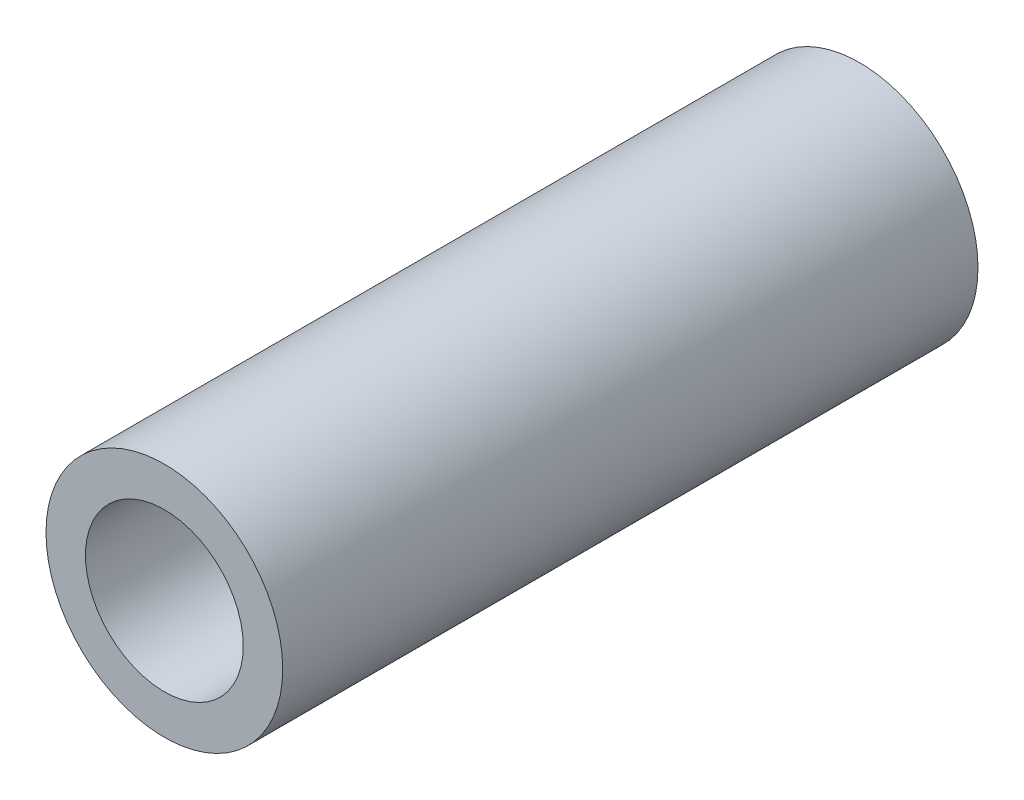
SolidWorks part; units mm, degrees
ref_plane "Front Plane" through (0, 0, 0) normal (0, 0, 1) x (1, 0, 0)
ref_plane "Top Plane" through (0, 0, 0) normal (0, 1, 0) x (1, 0, 0)
ref_plane "Right Plane" through (0, 0, 0) normal (1, 0, 0) x (0, 0, -1)
sketch "Эскиз1" plane through (0, 0, 0) normal (0, 0, 1) x (1, 0, 0)
  circle A2 centre (3.5, -0.4243) radius 0.4
  circle A3 centre (3.5, -0.4243) radius 0.6
extrude "Бобышка-Вытянуть1" add sketch "Эскиз1" along normal up to vertex (3.5249 mm away) contours A3 | A2
sketch "Эскиз2" plane through (0, 0, 3.5249) normal (0, 0, 1) x (1, 0, 0)
  point P0 (3.5, -0.4243)
